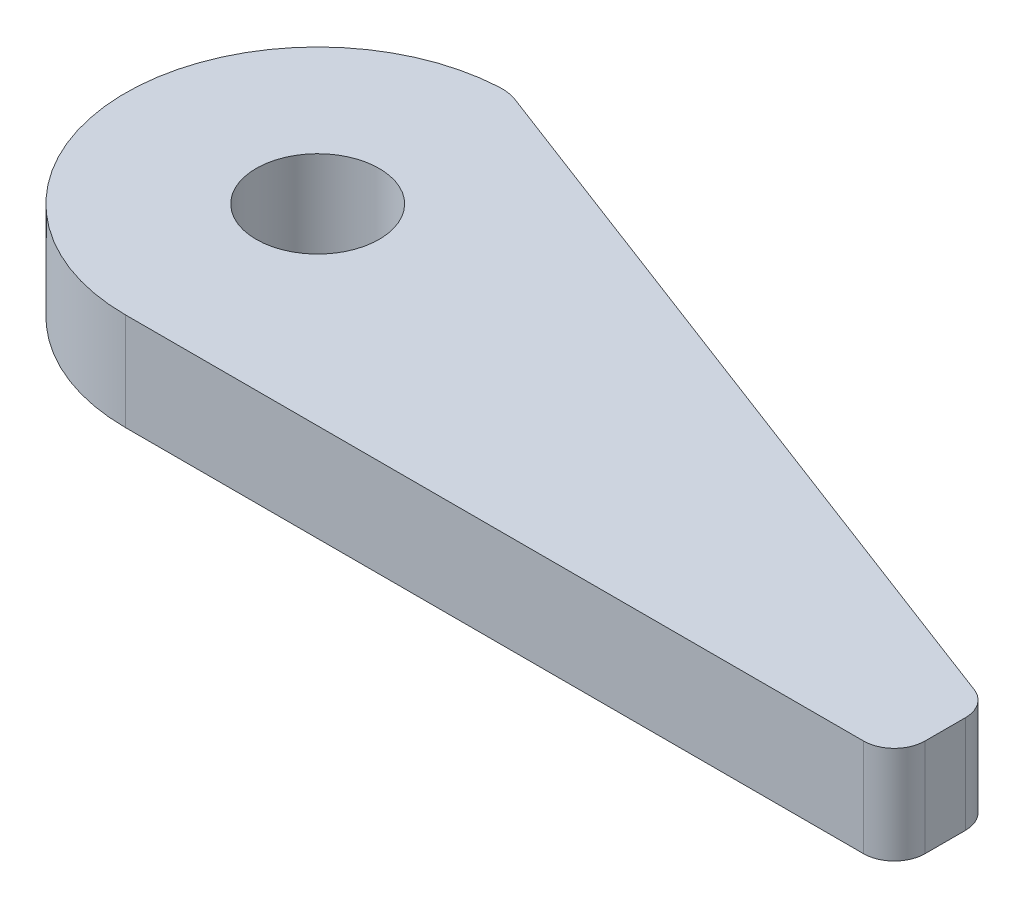
SolidWorks part; units mm, degrees
ref_plane "Front Plane" through (0, 0, 0) normal (0, 0, 1) x (1, 0, 0)
ref_plane "Top Plane" through (0, 0, 0) normal (0, 1, 0) x (1, 0, 0)
ref_plane "Right Plane" through (0, 0, 0) normal (1, 0, 0) x (0, 0, -1)
sketch "Sketch1" plane through (0, 0, 0) normal (0, 1, 0) x (1, 0, 0)
  line L0 (0, -12.5) -> (50, -12.5)
  line L1 (0, 12.5) -> (50, -6.5)
  line L2 (50, -6.5) -> (50, -12.5)
  arc A0 (0, 12.5) -> (0, -12.5) centre (0, 0) ccw
  circle A1 centre (0, 0) radius 4
  dimension "D1" = 25
  dimension "D4" = 8
  dimension "D2" = 50
  dimension "D3" = 6
extrude "Boss-Extrude1" add sketch "Sketch1" along normal blind 6.35
fillet "Fillet1" radius 2 2 edges at (50, 3.175, 12.5) (50, 3.175, 6.5)
fillet "Fillet2" radius 3 1 edges at (0, 3.175, -12.5)
